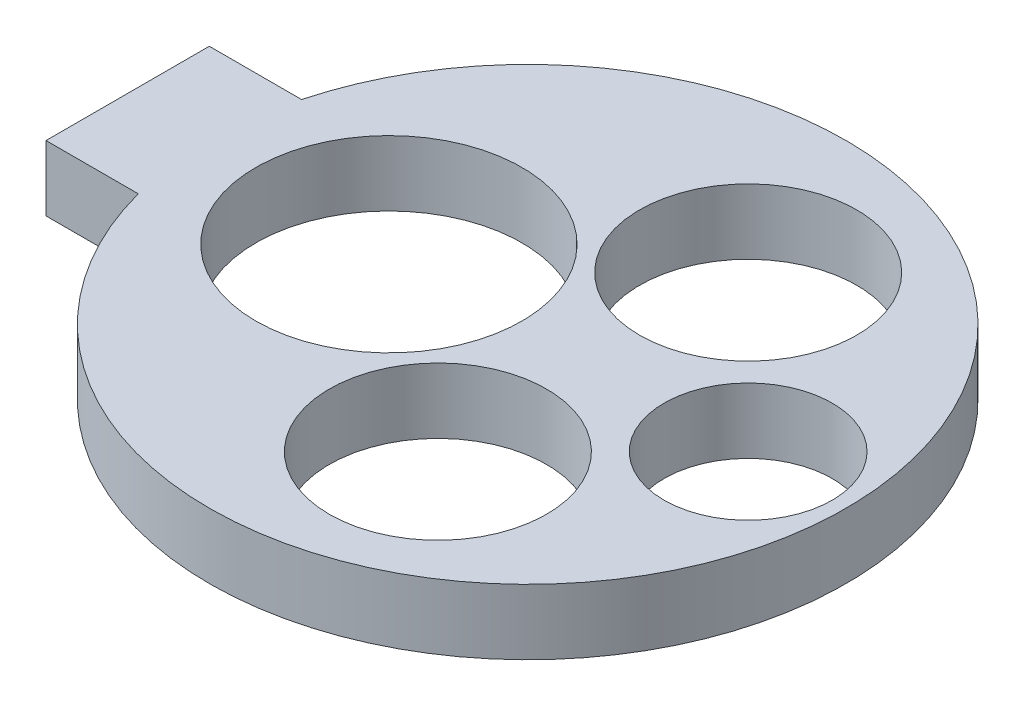
SolidWorks part; units mm, degrees
material "6061 Alloy"
ref_plane "Alzado" through (0, 0, 0) normal (0, 0, 1) x (1, 0, 0)
ref_plane "Planta" through (0, 0, 0) normal (0, 1, 0) x (1, 0, 0)
ref_plane "Vista lateral" through (0, 0, 0) normal (1, 0, 0) x (0, 0, -1)
ref_plane "Plane2" through (0, -2, 0) normal (0, 1, 0) x (1, 0, 0)
sketch "Sketch1" plane through (0, -2, 0) normal (0, 1, 0) x (1, 0, 0)
  circle A0 centre (0, 0) radius 19.5
  circle A1 centre (-8.5, 0) radius 8.15
  circle A2 centre (4, -9.5) radius 6.65
  circle A3 centre (4, 9.5) radius 6.65
  circle A4 centre (13.5, 0) radius 5.15
extrude "Disco_separador" add sketch "Sketch1" along normal blind 4
sketch "Sketch2" plane through (0, -2, 0) normal (0, 1, 0) x (1, 0, 0)
  line L0 (-24.5, -5) -> (-17.5, -5)
  line L1 (-17.5, -5) -> (-17.5, 5)
  line L2 (-17.5, 5) -> (-24.5, 5)
  line L3 (-24.5, 5) -> (-24.5, -5)
extrude "Pata_al_hueso" add sketch "Sketch2" along normal blind 4
